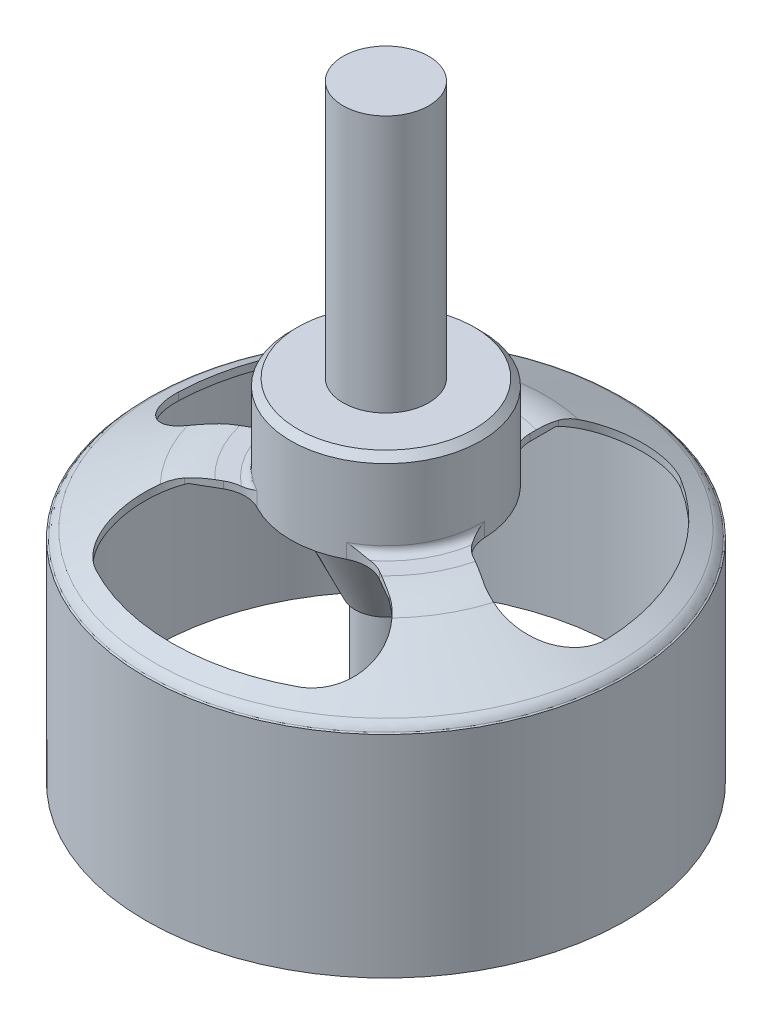
SolidWorks part; units mm, degrees
material "Cast Alloy Steel"
ref_plane "Front Plane" through (0, 0, 0) normal (0, 0, 1) x (1, 0, 0)
ref_plane "Top Plane" through (0, 0, 0) normal (0, 1, 0) x (1, 0, 0)
ref_plane "Right Plane" through (0, 0, 0) normal (1, 0, 0) x (0, 0, -1)
sketch "Sketch1" plane through (0, 0, 0) normal (0, 0, 1) x (1, 0, 0)
  line L0 (0, 0) -> (0, 43.4) construction
  line L1 (-14, 8) -> (-14, 20.3)
  line L2 (-14, 8) -> (-13.6, 8)
  line L3 (-5.55, 23.4) -> (-8.25, 23.4)
  line L4 (-1.8, 17.6) -> (-1.8, 43.4) construction
  line L5 (-1.8, 17.6) -> (0, 17.6)
  line L6 (-1.8, 17.6) -> (-4.3181, 23)
  line L7 (-8.25, 0) -> (-8.25, 23.4) construction
  line L8 (-8.25, 20.5) -> (-14, 20.5) construction
  line L9 (-14, 20.5) -> (-8.25, 23.4)
  line L10 (-5.55, 23.4) -> (-5.55, 28.4)
  line L11 (-14, 17.6) -> (0, 17.6) construction
  line L12 (-14, 0) -> (-14, 28.8581) construction
  line L13 (-1.8, 0) -> (-1.8, 43.4) construction
  line L14 (-5.55, 23) -> (-8.1548, 23) construction
  line L15 (-8.25, 0) -> (-8.25, 28.8581) construction
  line L17 (-14, 8) -> (0, 8) construction
  line L18 (-2.5, 28.4) -> (-5.55, 28.4)
  line L19 (0, 43.4) -> (-2.5, 43.4)
  line L20 (-5.55, 0) -> (-5.55, 28.8581) construction
  line L21 (0, 28.4) -> (-8.25, 28.4) construction
  line L22 (0, 23.4) -> (-8.25, 23.4) construction
  line L23 (-2.5, 28.4) -> (-2.5, 43.4)
  line L24 (-2.5, 0) -> (-2.5, 28.8581) construction
  line L25 (0, 0) -> (0, 28.8581) construction
  line L26 (-13.6, 8) -> (-14, 8)
  line L27 (0, 43.4) -> (-5.55, 43.4) construction
  line L28 (0, 28.4) -> (-5.55, 28.4) construction
  line L30 (0, 0) -> (0, 43.4)
  line L34 (-13.8199, 20.1429) -> (-8.1548, 23)
  line L38 (-4.3181, 23) -> (-8.1548, 23)
  line L39 (-13.6, 8) -> (-13.6, 20.3)
  arc A0 (-14, 20.3) -> (-14, 20.5) centre (-14, 20.4) ccw
  point P6 (-14, 23.4)
  point P7 (-12.5, 0)
  point P8 (-12.5, 28.8581)
  point P9 (0, 7.5)
  point P10 (-14, 7.5)
  point P13 (0, 20.5)
  point P33 (-5.2, 0)
  point P35 (-5.2, 43.4)
  point P36 (0, 2)
  point P38 (-12.5, 2)
  dimension "D15" = 0.4
  dimension "D2" = 15.4
  dimension "D3" = 1.8
  dimension "D4" = 9.6
  dimension "D6" = 25
  dimension "D1" = 14
  dimension "D5" = 8.25
  dimension "D7" = 5.55
  dimension "D8" = 5
  dimension "D9" = 15
  dimension "D10" = 2.5
revolve "Revolve1" add sketch "Sketch1" angle 360 about L30
fillet "Fillet2" radius 1 1 edges at (14, 20.5, 0)
fillet "Fillet3" radius 5 1 edges at (8.25, 23.4, 0)
fillet "Fillet4" radius 0.45 1 edges at (5.55, 23.4, 0)
chamfer "Chamfer1" distance 0.4 angle 45 1 edges at (5.55, 28.4, 0)
ref_plane "Plane1" through (0, 20.3, 0) normal (0, 1, 0) x (1, 0, 0)
sketch "Sketch4" plane through (0, 20.3, 0) normal (0, 1, 0) x (1, 0, 0)
  line L0 (0, 0) -> (0, 14)
  line L1 (0, 0) -> (8.0358, 11.4763)
  line L2 (0, 0) -> (-8.0358, 11.4763)
  circle A0 centre (0, 0) radius 14 construction
  circle A1 centre (0, 0) radius 14
  circle A2 centre (0, 0) radius 14.01
  dimension "D1" = 35
  dimension "D2" = 0.01
extrude "Boss-Extrude1" add sketch "Sketch4" along normal up to surface (12.3 mm away) contours L1 A2 L2 A1
sketch "Sketch5" plane through (0, 17.6, 0) normal (0, -1, 0) x (1, 0, 0)
  circle A0 centre (0, 0) radius 1.5
extrude "Boss-Extrude2" add sketch "Sketch5" along normal blind 15
sketch "Sketch6" plane through (0, 28.4, 0) normal (0, 1, 0) x (1, 0, 0)
  line L0 (0, 0) -> (0, 13.4894) construction
  line L1 (0, 0) -> (11.6821, -6.7447) construction
  line L2 (0, 0) -> (-11.6821, -6.7447) construction
  line L3 (2, 6.4033) -> (2, 8.0652)
  line L4 (-6.5454, -1.4696) -> (-7.9847, -2.3006)
  line L5 (4.5454, -4.9337) -> (5.9847, -5.7647)
  line L6 (-2, 6.4033) -> (-2, 8.0652)
  line L7 (-4.5454, -4.9337) -> (-5.9847, -5.7647)
  line L8 (6.5454, -1.4696) -> (7.9847, -2.3006)
  line L10 (-1, 1.7321) -> (-12.6821, -5.0126) construction
  line L11 (-2, 0) -> (-2, 13.4894) construction
  line L12 (1, 1.7321) -> (12.6821, -5.0126) construction
  line L13 (2, 0) -> (2, 13.4894) construction
  line L14 (-1, -1.7321) -> (10.6821, -8.4767) construction
  line L15 (1, -1.7321) -> (-10.6821, -8.4767) construction
  circle A0 centre (0, 0) radius 5.55 construction
  arc A1 (-2.6062, -4.9) -> (2.6062, -4.9) centre (0, 0) ccw
  circle A2 centre (0, 0) radius 13.4894 construction
  circle A3 centre (0, 0) radius 13.4894
  arc A4 (-6.5807, 10.615) -> (-12.4832, 0.3916) centre (0, 0) ccw
  arc A5 (-2.9404, 4.7071) -> (-5.5466, 0.1929) centre (0, 0) ccw
  arc A6 (5.5466, 0.1929) -> (2.9404, 4.7071) centre (0, 0) ccw
  arc A7 (-5.9025, -11.0066) -> (5.9025, -11.0066) centre (0, 0) ccw
  circle A8 centre (0, 0) radius 12.4894 construction
  arc A9 (12.4832, 0.3916) -> (6.5807, 10.615) centre (0, 0) ccw
  arc A10 (2, 8.0652) -> (6.5807, 10.615) centre (5, 8.0652) cw
  arc A11 (12.4832, 0.3916) -> (7.9847, -2.3006) centre (9.4847, 0.2975) cw
  arc A12 (5.9847, -5.7647) -> (5.9025, -11.0066) centre (4.4847, -8.3627) cw
  arc A13 (-5.9025, -11.0066) -> (-5.9847, -5.7647) centre (-4.4847, -8.3627) cw
  arc A14 (-7.9847, -2.3006) -> (-12.4832, 0.3916) centre (-9.4847, 0.2975) cw
  arc A15 (-6.5807, 10.615) -> (-2, 8.0652) centre (-5, 8.0652) cw
  arc A16 (2.9404, 4.7071) -> (2, 6.4033) centre (4, 6.4033) cw
  arc A17 (-2, 6.4033) -> (-2.9404, 4.7071) centre (-4, 6.4033) cw
  arc A18 (-5.5466, 0.1929) -> (-6.5454, -1.4696) centre (-7.5454, 0.2624) cw
  arc A19 (-4.5454, -4.9337) -> (-2.6062, -4.9) centre (-3.5454, -6.6658) cw
  arc A20 (2.6062, -4.9) -> (4.5454, -4.9337) centre (3.5454, -6.6658) cw
  arc A21 (5.5466, 0.1929) -> (6.5454, -1.4696) centre (7.5454, 0.2624) ccw
  point P27 (12.4894, 0)
  point P38 (11.6765, -4.432)
  point P47 (-2, 12.3282)
  point P52 (-2, 5.1771)
  point P61 (5.4835, -0.8565)
  dimension "D2" = 120
  dimension "D6" = 3
  dimension "D7" = 2
  dimension "D8" = 2
  dimension "D9" = 2
  dimension "D1" = 120
  dimension "D3" = 2
  dimension "D4" = 2
  dimension "D5" = 1
extrude "Cut-Extrude1" cut sketch "Sketch6" against normal blind 15 contours A18 A5 A17 L6 A15 A4 A14 L4 | A6 A21 L8 A11 A9 A10 L3 A16 | A20 A1 A19 L7 A13 A7 A12 L5
